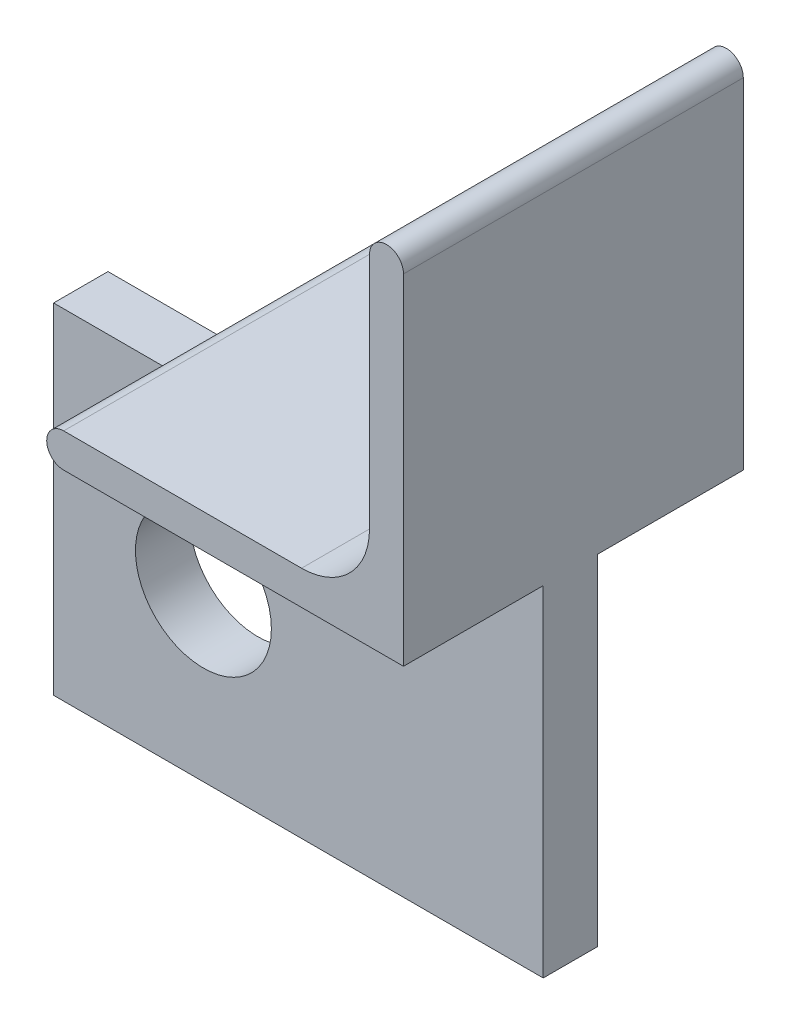
SolidWorks part; units mm, degrees
ref_plane "Alzado" through (0, 0, 0) normal (0, 0, 1) x (1, 0, 0)
ref_plane "Planta" through (0, 0, 0) normal (0, 1, 0) x (1, 0, 0)
ref_plane "Vista lateral" through (0, 0, 0) normal (1, 0, 0) x (0, 0, -1)
sketch "Croquis1" plane through (0, 0, 0) normal (0, 0, 1) x (1, 0, 0)
  line L0 (0, 0) -> (50, 0)
  line L1 (50, 0) -> (50, 50)
  line L2 (0, 5) -> (35, 5)
  line L3 (45, 15) -> (45, 50)
  line L4 (0, 5) -> (45, 5) construction
  line L5 (45, 5) -> (45, 50) construction
  arc A0 (0, 0) -> (0, 5) centre (0, 2.5) cw
  arc A1 (50, 50) -> (45, 50) centre (47.5, 50) ccw
  arc A2 (35, 5) -> (45, 15) centre (35, 15) ccw
  dimension "D2" = 10
  dimension "D1" = 5
extrude "Saliente-Extruir1" add sketch "Croquis1" along normal mid plane 50
sketch "Croquis2" plane through (0, 0, 0) normal (0, -1, 0) x (1, 0, 0)
  line L1 (-22.0449, 4.44) -> (50, 4.44)
  line L2 (-22.0449, 4.44) -> (-22.0449, -3.56)
  line L3 (-22.0449, -3.56) -> (50, -3.56)
  line L4 (50, 4.44) -> (50, -3.56)
  point P6 (0, 0)
  dimension "D1" = 8
extrude "Saliente-Extruir2" add sketch "Croquis2" along normal blind 50
sketch "Croquis3" plane through (0, 0, 4.44) normal (0, 0, 1) x (1, 0, 0)
  circle A0 centre (0, -25.5107) radius 10
  point P2 (0, -25.5107)
extrude "Cortar-Extruir1" cut sketch "Croquis3" against normal blind 50
